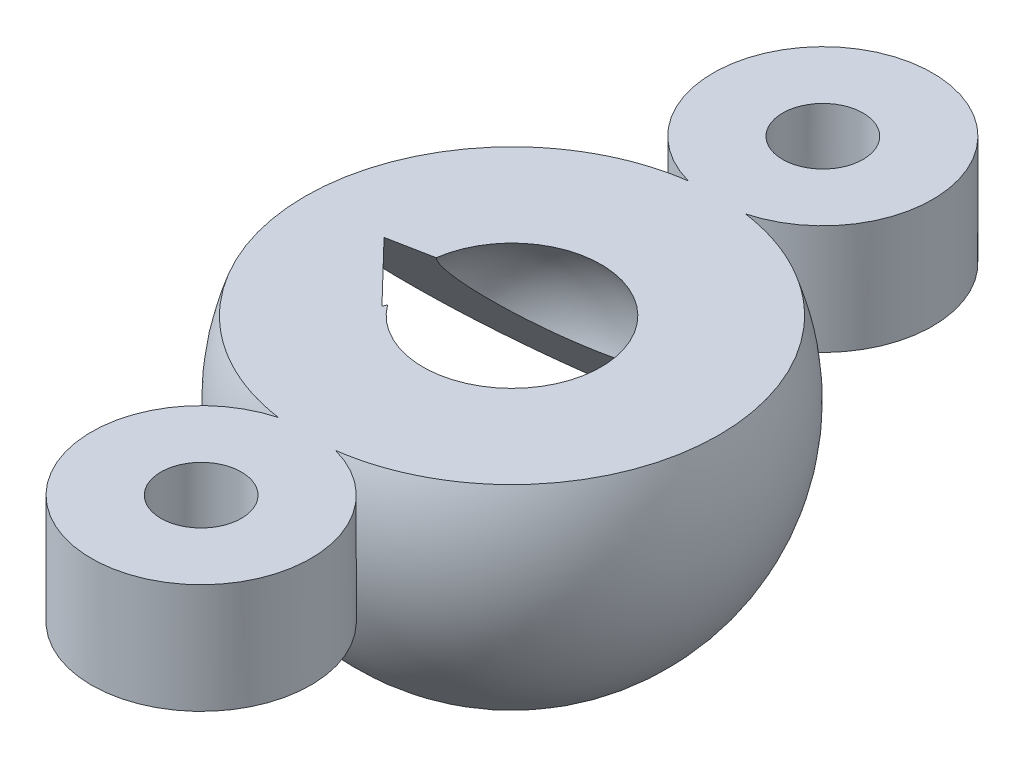
SolidWorks part; units mm, degrees
other "Compression Link 1 Fixed Ball Retainer"
ref_plane "Front Plane" through (0, 0, 0) normal (0, 0, 1) x (1, 0, 0)
ref_plane "Top Plane" through (0, 0, 0) normal (0, 1, 0) x (1, 0, 0)
ref_plane "Right Plane" through (0, 0, 0) normal (1, 0, 0) x (0, 0, -1)
sketch3d "Retainer Feature 1 axis line"
  line L0 (-26.2917, -73, -10) -> (-26.2917, -73, 10) construction
ref_axis "Retainer Feature 1 axis" through (-26.2917, -73, -10) along (0, 0, 1)
sketch3d "Retainer Feature 1 profile datum points"
  point P0 (-26.2917, -73, 0)
  point P1 (-16.2917, -73, 0)
  point P2 (-26.2917, -73, 10)
ref_plane "Retainer Feature 1 profile plane" through (0, -73, 0) normal (0, -1, 0) x (-1, 0, 0)
sketch "Retainer Feature 1 profile" plane through (0, -73, 0) normal (0, -1, 0) x (-1, 0, 0)
  line L0 (26.2917, -6) -> (26.2917, 6)
  arc A0 (26.2917, 6) -> (26.2917, -6) centre (26.2917, 0) ccw
revolve "Retainer Feature 1" add sketch "Retainer Feature 1 profile" angle 360 about axis through (-26.2917, -73, -10) along (0, 0, 1)
sketch3d "Retainer Feature 2 profile datum points"
  point P0 (-33.2917, -71, -7)
  point P1 (-23.2917, -71, -7)
  point P2 (-33.2917, -61, -7)
ref_plane "Retainer Feature 2 profile plane" through (0, 0, -7) normal (0, 0, 1) x (1, 0, 0)
sketch "Retainer Feature 2 profile" plane through (0, 0, -7) normal (0, 0, 1) x (1, 0, 0)
  line L0 (-33.2917, -71) -> (-19.2917, -71)
  line L1 (-19.2917, -71) -> (-19.2917, -66)
  line L2 (-19.2917, -66) -> (-33.2917, -66)
  line L3 (-33.2917, -66) -> (-33.2917, -71)
extrude "Retainer Feature 2" cut sketch "Retainer Feature 2 profile" along normal blind 14
sketch3d "Retainer Feature 3 profile datum points"
  point P0 (-26.2917, -71, -8.5)
  point P1 (-16.2917, -71, -8.5)
  point P2 (-26.2917, -71, 1.5)
ref_plane "Retainer Feature 3 profile plane" through (0, -71, 0) normal (0, -1, 0) x (-1, 0, 0)
sketch "Retainer Feature 3 profile" plane through (0, -71, 0) normal (0, -1, 0) x (-1, 0, 0)
  circle A0 centre (26.2917, 8.5) radius 3
extrude "Retainer Feature 3" add sketch "Retainer Feature 3 profile" along normal blind 3
sketch3d "Retainer Feature 4 profile datum points"
  point P0 (-26.2917, -71, 8.5)
  point P1 (-16.2917, -71, 8.5)
  point P2 (-26.2917, -71, 18.5)
ref_plane "Retainer Feature 4 profile plane" through (0, -71, 0) normal (0, -1, 0) x (-1, 0, 0)
sketch "Retainer Feature 4 profile" plane through (0, -71, 0) normal (0, -1, 0) x (-1, 0, 0)
  circle A0 centre (26.2917, -8.5) radius 3
extrude "Retainer Feature 4" add sketch "Retainer Feature 4 profile" along normal blind 3
sketch3d "Retainer Feature 5 axis line"
  line L0 (-26.2917, -73, -10) -> (-26.2917, -73, 10) construction
ref_axis "Retainer Feature 5 axis" through (-26.2917, -73, -10) along (0, 0, 1)
sketch3d "Retainer Feature 5 profile datum points"
  point P0 (-26.2917, -73, 0)
  point P1 (-16.2917, -73, 0)
  point P2 (-26.2917, -73, 10)
ref_plane "Retainer Feature 5 profile plane" through (0, -73, 0) normal (0, -1, 0) x (-1, 0, 0)
sketch "Retainer Feature 5 profile" plane through (0, -73, 0) normal (0, -1, 0) x (-1, 0, 0)
  line L0 (26.2917, -3.15) -> (26.2917, 3.15)
  arc A0 (26.2917, 3.15) -> (26.2917, -3.15) centre (26.2917, 0) ccw
revolve "Retainer Feature 5" cut sketch "Retainer Feature 5 profile" angle 360 about axis through (-26.2917, -73, -10) along (0, 0, 1)
sketch3d "Retainer Feature 6 profile datum points"
  point P0 (-26.2917, -70, -8.5)
  point P1 (-16.2917, -70, -8.5)
  point P2 (-26.2917, -70, 1.5)
ref_plane "Retainer Feature 6 profile plane" through (0, -70, 0) normal (0, -1, 0) x (-1, 0, 0)
sketch "Retainer Feature 6 profile" plane through (0, -70, 0) normal (0, -1, 0) x (-1, 0, 0)
  circle A0 centre (26.2917, 8.5) radius 1.1
extrude "Retainer Feature 6" cut sketch "Retainer Feature 6 profile" along normal blind 4.25
sketch3d "Retainer Feature 7 profile datum points"
  point P0 (-26.2917, -72.8, -8.5)
  point P1 (-16.2917, -72.8, -8.5)
  point P2 (-26.2917, -72.8, 1.5)
ref_plane "Retainer Feature 7 profile plane" through (0, -72.8, 0) normal (0, -1, 0) x (-1, 0, 0)
sketch "Retainer Feature 7 profile" plane through (0, -72.8, 0) normal (0, -1, 0) x (-1, 0, 0)
  circle A0 centre (26.2917, 8.5) radius 2.1
extrude "Retainer Feature 7" cut sketch "Retainer Feature 7 profile" along normal blind 1.45
sketch3d "Retainer Feature 8 profile datum points"
  point P0 (-26.2917, -70, 8.5)
  point P1 (-16.2917, -70, 8.5)
  point P2 (-26.2917, -70, 18.5)
ref_plane "Retainer Feature 8 profile plane" through (0, -70, 0) normal (0, -1, 0) x (-1, 0, 0)
sketch "Retainer Feature 8 profile" plane through (0, -70, 0) normal (0, -1, 0) x (-1, 0, 0)
  circle A0 centre (26.2917, -8.5) radius 1.1
extrude "Retainer Feature 8" cut sketch "Retainer Feature 8 profile" along normal blind 4.25
sketch3d "Retainer Feature 9 profile datum points"
  point P0 (-26.2917, -72.8, 8.5)
  point P1 (-16.2917, -72.8, 8.5)
  point P2 (-26.2917, -72.8, 18.5)
ref_plane "Retainer Feature 9 profile plane" through (0, -72.8, 0) normal (0, -1, 0) x (-1, 0, 0)
sketch "Retainer Feature 9 profile" plane through (0, -72.8, 0) normal (0, -1, 0) x (-1, 0, 0)
  circle A0 centre (26.2917, -8.5) radius 2.1
extrude "Retainer Feature 9" cut sketch "Retainer Feature 9 profile" along normal blind 1.45
sketch3d "Middle Right Fixed Compression Ball Retainer 1 Angular Clearance Sketch 21 datum points"
  point P0 (-26.2917, -73, 0)
  point P1 (-20.2307, -78.3859, -5.853)
  point P2 (-24.834, -79.4818, 7.474)
ref_plane "Middle Right Fixed Compression Ball Retainer 1 Angular Clearance Sketch 21 plane" through (-46.8018, -32.2203, -18.8155) normal (-0.7819, -0.5383, -0.3144) x (-0.2589, -0.1783, 0.9493)
sketch "Middle Right Fixed Compression Ball Retainer 1 Angular Clearance Sketch 21" plane through (-46.8018, -32.2203, -18.8155) normal (-0.7819, -0.5383, -0.3144) x (-0.2589, -0.1783, 0.9493)
  line L0 (20.2973, -41.529) -> (16.3514, -46.5678)
  line L1 (16.3514, -46.5678) -> (19.3432, -48.9107)
  line L2 (19.3432, -48.9107) -> (23.2891, -43.8719)
  line L3 (23.2891, -43.8719) -> (20.2973, -41.529)
extrude "Retainer Feature 12" cut sketch "Middle Right Fixed Compression Ball Retainer 1 Angular Clearance Sketch 21" along normal blind 10
